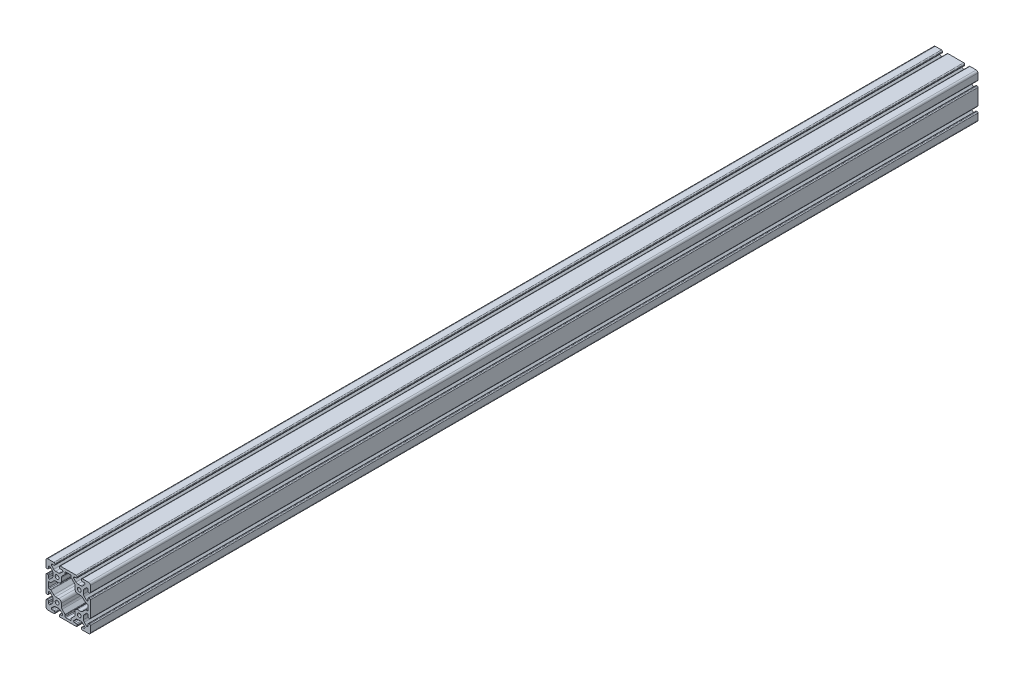
SolidWorks part; units mm, degrees
material "6061 Alloy"
ref_plane "Front Plane" through (0, 0, 0) normal (0, 0, 1) x (1, 0, 0)
ref_plane "Top Plane" through (0, 0, 0) normal (0, 1, 0) x (1, 0, 0)
ref_plane "Right Plane" through (0, 0, 0) normal (1, 0, 0) x (0, 0, -1)
sketch "Sketch1" plane through (0, 0, 0) normal (0, 0, 1) x (1, 0, 0)
  line L0 (0, -40) -> (0, 40) construction
  line L1 (0, 0) -> (-43.5804, 43.5804) construction
  line L2 (-20, 20) -> (-47.7323, 20) construction
  line L3 (-20, 20) -> (3.796, 43.796) construction
  line L4 (-20, 20) -> (-20, 43.5758) construction
  line L5 (-20, -27.7) -> (-20, -47.5576) construction
  line L7 (-36.8718, 24) -> (-28.8718, 24) construction
  line L8 (-36.8718, 24) -> (-36.8718, 16) construction
  line L9 (-36.8718, 16) -> (-28.8718, 16) construction
  line L10 (-28.8718, 24) -> (-28.8718, 16) construction
  line L11 (-36.8718, 24) -> (-28.8718, 16) construction
  line L12 (-36.8718, 16) -> (-28.8718, 24) construction
  line L131 (29.0912, 26.0365) -> (33.0827, 30.028)
  line L132 (27.7, 17.3222) -> (27.7, 22.6778)
  line L133 (29.0912, 13.9635) -> (33.0827, 9.972)
  line L134 (33.6201, 9.7494) -> (34.11, 9.7494)
  line L135 (35.68, 11.3194) -> (35.68, 14.2221)
  line L136 (37.25, 15.7921) -> (38.43, 15.7921)
  line L137 (40, 14.2221) -> (40, 7.0214)
  line L138 (40, 7.0214) -> (40, -7.0214)
  line L139 (40, -7.0214) -> (40, -14.2221)
  line L140 (38.43, -15.7921) -> (37.25, -15.7921)
  line L141 (35.68, -14.2221) -> (35.68, -11.3194)
  line L142 (33.6201, -9.7494) -> (34.11, -9.7494)
  line L143 (29.0912, -13.9635) -> (33.0827, -9.972)
  line L144 (27.7, -22.6778) -> (27.7, -17.3222)
  line L145 (29.0912, -26.0365) -> (33.0827, -30.028)
  line L146 (33.6201, -30.2506) -> (34.11, -30.2506)
  line L147 (35.68, -28.6806) -> (35.68, -25.7779)
  line L148 (37.25, -24.2079) -> (38.43, -24.2079)
  line L149 (40, -25.7779) -> (40, -33.0259)
  line L150 (40, -33.0259) -> (40, -36.83)
  line L151 (36.83, -40) -> (32.9998, -40)
  line L152 (32.9998, -40) -> (25.5696, -40)
  line L153 (23.9996, -38.43) -> (23.9996, -37.25)
  line L154 (25.5696, -35.68) -> (28.4723, -35.68)
  line L155 (30.0413, -34.0552) -> (30.0171, -33.3605)
  line L156 (29.7949, -32.8496) -> (26.0365, -29.0912)
  line L157 (17.3222, -27.7) -> (22.6778, -27.7)
  line L158 (10.035, -33.0197) -> (13.9635, -29.0912)
  line L159 (9.8124, -33.8926) -> (9.8124, -33.5571)
  line L160 (11.3824, -35.4626) -> (14.4246, -35.4626)
  line L161 (15.9946, -37.0326) -> (15.9946, -38.43)
  line L162 (14.4246, -40) -> (6.9987, -40)
  line L163 (6.9987, -40) -> (-6.9987, -40)
  line L164 (-6.9987, -40) -> (-14.4292, -40)
  line L165 (-15.9992, -38.43) -> (-15.9992, -37.25)
  line L166 (-14.4292, -35.68) -> (-11.5265, -35.68)
  line L167 (-9.9574, -34.0552) -> (-9.9816, -33.3618)
  line L168 (-10.2038, -32.8509) -> (-13.9635, -29.0912)
  line L169 (-22.6778, -27.7) -> (-17.3222, -27.7)
  line L170 (-30.028, -33.0827) -> (-26.0365, -29.0912)
  line L171 (-30.2506, -34.11) -> (-30.2506, -33.6201)
  line L172 (-28.6806, -35.68) -> (-25.7231, -35.68)
  line L173 (-24.1531, -37.25) -> (-24.1531, -38.43)
  line L174 (-25.7231, -40) -> (-33, -40)
  line L175 (-33, -40) -> (-36.83, -40)
  line L176 (-40, -36.83) -> (-40, -33.0191)
  line L177 (-40, -33.0191) -> (-40, -25.591)
  line L178 (-38.43, -24.021) -> (-37.25, -24.021)
  line L179 (-35.68, -28.4937) -> (-35.68, -25.591)
  line L180 (-34.0552, -30.0627) -> (-33.3827, -30.0392)
  line L181 (-32.8718, -29.8171) -> (-29.0912, -26.0365)
  line L182 (-27.7, -22.6778) -> (-27.7, -17.3222)
  line L183 (-29.0912, -13.9635) -> (-33.0827, -9.972)
  line L184 (-34.11, -9.7494) -> (-33.6201, -9.7494)
  line L185 (-35.68, -11.3194) -> (-35.68, -14.4473)
  line L186 (-38.43, -16.0173) -> (-37.25, -16.0173)
  line L187 (-40, -14.4473) -> (-40, -7.0169)
  line L188 (-40, -7.0169) -> (-40, 7.0169)
  line L189 (-40, 7.0169) -> (-40, 14.1348)
  line L190 (-38.1948, 15.94) -> (-36.9772, 15.94)
  line L191 (-35.68, 11.3194) -> (-35.68, 14.6428)
  line L192 (-34.11, 9.7494) -> (-33.6201, 9.7494)
  line L193 (-33.0827, 9.972) -> (-29.0912, 13.9635)
  line L194 (-27.7, 17.3222) -> (-27.7, 22.6778)
  line L195 (-29.0912, 26.0365) -> (-33.0827, 30.028)
  line L196 (-34.11, 30.2506) -> (-33.6201, 30.2506)
  line L197 (-35.68, 28.6806) -> (-35.68, 25.3572)
  line L198 (-38.1948, 24.06) -> (-36.9772, 24.06)
  line L199 (-40, 25.8652) -> (-40, 33.3181)
  line L200 (-40, 33.3181) -> (-40, 36.83)
  line L201 (-36.83, 40) -> (-33.0314, 40)
  line L202 (-33.0314, 40) -> (-25.8652, 40)
  line L203 (-24.06, 36.9772) -> (-24.06, 38.1948)
  line L204 (-25.3572, 35.68) -> (-28.7018, 35.68)
  line L205 (-30.285, 33.6069) -> (-30.285, 34.0968)
  line L206 (-30.0961, 33.1508) -> (-26.0365, 29.0912)
  line L207 (-22.6778, 27.7) -> (-17.3222, 27.7)
  line L208 (-13.9635, 29.0912) -> (-9.9039, 33.1508)
  line L209 (-9.715, 33.6069) -> (-9.715, 34.0968)
  line L210 (-14.6428, 35.68) -> (-11.2982, 35.68)
  line L211 (-15.94, 36.9772) -> (-15.94, 38.1948)
  line L212 (-14.1348, 40) -> (-6.9844, 40)
  line L213 (-6.9844, 40) -> (6.9844, 40)
  line L214 (6.9844, 40) -> (14.1348, 40)
  line L215 (15.94, 36.9772) -> (15.94, 38.1948)
  line L216 (14.6428, 35.68) -> (11.2982, 35.68)
  line L217 (9.715, 33.6069) -> (9.715, 34.0968)
  line L218 (9.9039, 33.1508) -> (13.9635, 29.0912)
  line L219 (17.3222, 27.7) -> (22.6778, 27.7)
  line L220 (26.0365, 29.0912) -> (30.028, 33.0827)
  line L221 (30.2506, 33.6201) -> (30.2506, 34.11)
  line L222 (25.5409, 35.679) -> (28.6258, 35.679)
  line L223 (23.9709, 37.249) -> (23.9709, 38.43)
  line L224 (25.5409, 40) -> (36.83, 40)
  line L226 (40, 36.83) -> (40, 32.9339)
  line L227 (40, 32.9339) -> (40, 25.7779)
  line L228 (38.43, 24.2079) -> (37.0956, 24.2079)
  line L229 (35.5256, 25.7779) -> (35.5256, 28.6806)
  line L230 (33.6201, 30.2506) -> (33.9556, 30.2506)
  line L231 (17.07, 12.32) -> (22.6578, 12.32)
  line L232 (26.0165, 10.9288) -> (31.1439, 5.8014)
  line L233 (32.0419, 5.4294) -> (34.41, 5.4294)
  line L234 (35.68, -4.1594) -> (35.68, 4.1594)
  line L235 (32.0419, -5.4294) -> (34.41, -5.4294)
  line L236 (26.0165, -10.9288) -> (31.1439, -5.8014)
  line L237 (17.07, -12.32) -> (22.6578, -12.32)
  line L238 (12.32, -22.6578) -> (12.32, -17.07)
  line L239 (5.8014, -31.1439) -> (10.9288, -26.0165)
  line L240 (5.4294, -34.41) -> (5.4294, -32.0419)
  line L241 (-4.1594, -35.68) -> (4.1594, -35.68)
  line L242 (-5.4294, -34.41) -> (-5.4294, -32.0419)
  line L243 (-5.8014, -31.1439) -> (-10.9288, -26.0165)
  line L244 (-12.32, -22.6578) -> (-12.32, -17.07)
  line L245 (-22.6578, -12.32) -> (-17.07, -12.32)
  line L246 (-26.0165, -10.9288) -> (-31.1439, -5.8014)
  line L247 (-34.41, -5.4294) -> (-32.0419, -5.4294)
  line L248 (-35.68, -4.1594) -> (-35.68, 4.1594)
  line L249 (-34.41, 5.4294) -> (-32.0419, 5.4294)
  line L250 (-31.1439, 5.8014) -> (-26.0165, 10.9288)
  line L251 (-22.6578, 12.32) -> (-17.07, 12.32)
  line L252 (-12.32, 17.07) -> (-12.32, 22.6578)
  line L253 (-10.9288, 26.0165) -> (-5.8014, 31.1439)
  line L254 (-5.4294, 32.0419) -> (-5.4294, 34.41)
  line L255 (-4.1594, 35.68) -> (4.1594, 35.68)
  line L256 (5.4294, 32.0419) -> (5.4294, 34.41)
  line L257 (5.8014, 31.1439) -> (10.9288, 26.0165)
  line L258 (12.32, 17.07) -> (12.32, 22.6578)
  line L260 (-40, 0) -> (40, 0) construction
  circle A0 centre (-32.8718, 20) radius 4 construction
  circle A116 centre (-20, 20) radius 3.4
  circle A117 centre (20, 20) radius 3.4
  circle A118 centre (20, -20) radius 3.4
  circle A119 centre (-20, -20) radius 3.4
  arc A120 (29.0912, 26.0365) -> (27.7, 22.6778) centre (32.45, 22.6778) ccw
  arc A121 (27.7, 17.3222) -> (29.0912, 13.9635) centre (32.45, 17.3222) ccw
  arc A122 (33.0827, 9.972) -> (33.6201, 9.7494) centre (33.6201, 10.5094) ccw
  arc A123 (34.11, 9.7494) -> (35.68, 11.3194) centre (34.11, 11.3194) ccw
  arc A124 (37.25, 15.7921) -> (35.68, 14.2221) centre (37.25, 14.2221) ccw
  arc A125 (40, 14.2221) -> (38.43, 15.7921) centre (38.43, 14.2221) ccw
  arc A126 (38.43, -15.7921) -> (40, -14.2221) centre (38.43, -14.2221) ccw
  arc A127 (35.68, -14.2221) -> (37.25, -15.7921) centre (37.25, -14.2221) ccw
  arc A128 (35.68, -11.3194) -> (34.11, -9.7494) centre (34.11, -11.3194) ccw
  arc A129 (33.6201, -9.7494) -> (33.0827, -9.972) centre (33.6201, -10.5094) ccw
  arc A130 (29.0912, -13.9635) -> (27.7, -17.3222) centre (32.45, -17.3222) ccw
  arc A131 (27.7, -22.6778) -> (29.0912, -26.0365) centre (32.45, -22.6778) ccw
  arc A132 (33.0827, -30.028) -> (33.6201, -30.2506) centre (33.6201, -29.4906) ccw
  arc A133 (34.11, -30.2506) -> (35.68, -28.6806) centre (34.11, -28.6806) ccw
  arc A134 (37.25, -24.2079) -> (35.68, -25.7779) centre (37.25, -25.7779) ccw
  arc A135 (40, -25.7779) -> (38.43, -24.2079) centre (38.43, -25.7779) ccw
  arc A136 (36.83, -40) -> (40, -36.83) centre (36.83, -36.83) ccw
  arc A137 (23.9996, -38.43) -> (25.5696, -40) centre (25.5696, -38.43) ccw
  arc A138 (25.5696, -35.68) -> (23.9996, -37.25) centre (25.5696, -37.25) ccw
  arc A139 (28.4723, -35.68) -> (30.0413, -34.0552) centre (28.4723, -34.11) ccw
  arc A140 (30.0171, -33.3605) -> (29.7949, -32.8496) centre (29.2575, -33.387) ccw
  arc A141 (26.0365, -29.0912) -> (22.6778, -27.7) centre (22.6778, -32.45) ccw
  arc A142 (17.3222, -27.7) -> (13.9635, -29.0912) centre (17.3222, -32.45) ccw
  arc A143 (10.035, -33.0197) -> (9.8124, -33.5571) centre (10.5724, -33.5571) ccw
  arc A144 (9.8124, -33.8926) -> (11.3824, -35.4626) centre (11.3824, -33.8926) ccw
  arc A145 (15.9946, -37.0326) -> (14.4246, -35.4626) centre (14.4246, -37.0326) ccw
  arc A146 (14.4246, -40) -> (15.9946, -38.43) centre (14.4246, -38.43) ccw
  arc A147 (-15.9992, -38.43) -> (-14.4292, -40) centre (-14.4292, -38.43) ccw
  arc A148 (-14.4292, -35.68) -> (-15.9992, -37.25) centre (-14.4292, -37.25) ccw
  arc A149 (-11.5265, -35.68) -> (-9.9574, -34.0552) centre (-11.5265, -34.11) ccw
  arc A150 (-9.9816, -33.3618) -> (-10.2038, -32.8509) centre (-10.7412, -33.3883) ccw
  arc A151 (-13.9635, -29.0912) -> (-17.3222, -27.7) centre (-17.3222, -32.45) ccw
  arc A152 (-22.6778, -27.7) -> (-26.0365, -29.0912) centre (-22.6778, -32.45) ccw
  arc A153 (-30.028, -33.0827) -> (-30.2506, -33.6201) centre (-29.4906, -33.6201) ccw
  arc A154 (-30.2506, -34.11) -> (-28.6806, -35.68) centre (-28.6806, -34.11) ccw
  arc A155 (-24.1531, -37.25) -> (-25.7231, -35.68) centre (-25.7231, -37.25) ccw
  arc A156 (-25.7231, -40) -> (-24.1531, -38.43) centre (-25.7231, -38.43) ccw
  arc A157 (-40, -36.83) -> (-36.83, -40) centre (-36.83, -36.83) ccw
  arc A158 (-38.43, -24.021) -> (-40, -25.591) centre (-38.43, -25.591) ccw
  arc A159 (-35.68, -25.591) -> (-37.25, -24.021) centre (-37.25, -25.591) ccw
  arc A160 (-35.68, -28.4937) -> (-34.0552, -30.0627) centre (-34.11, -28.4937) ccw
  arc A161 (-33.3827, -30.0392) -> (-32.8718, -29.8171) centre (-33.4092, -29.2797) ccw
  arc A162 (-29.0912, -26.0365) -> (-27.7, -22.6778) centre (-32.45, -22.6778) ccw
  arc A163 (-27.7, -17.3222) -> (-29.0912, -13.9635) centre (-32.45, -17.3222) ccw
  arc A164 (-33.0827, -9.972) -> (-33.6201, -9.7494) centre (-33.6201, -10.5094) ccw
  arc A165 (-34.11, -9.7494) -> (-35.68, -11.3194) centre (-34.11, -11.3194) ccw
  arc A166 (-37.25, -16.0173) -> (-35.68, -14.4473) centre (-37.25, -14.4473) ccw
  arc A167 (-40, -14.4473) -> (-38.43, -16.0173) centre (-38.43, -14.4473) ccw
  arc A168 (-38.1948, 15.94) -> (-40, 14.1348) centre (-38.1948, 14.1348) ccw
  arc A169 (-35.68, 14.6428) -> (-36.9772, 15.94) centre (-36.9772, 14.6428) ccw
  arc A170 (-35.68, 11.3194) -> (-34.11, 9.7494) centre (-34.11, 11.3194) ccw
  arc A171 (-33.6201, 9.7494) -> (-33.0827, 9.972) centre (-33.6201, 10.5094) ccw
  arc A172 (-29.0912, 13.9635) -> (-27.7, 17.3222) centre (-32.45, 17.3222) ccw
  arc A173 (-27.7, 22.6778) -> (-29.0912, 26.0365) centre (-32.45, 22.6778) ccw
  arc A174 (-33.0827, 30.028) -> (-33.6201, 30.2506) centre (-33.6201, 29.4906) ccw
  arc A175 (-34.11, 30.2506) -> (-35.68, 28.6806) centre (-34.11, 28.6806) ccw
  arc A176 (-36.9772, 24.06) -> (-35.68, 25.3572) centre (-36.9772, 25.3572) ccw
  arc A177 (-40, 25.8652) -> (-38.1948, 24.06) centre (-38.1948, 25.8652) ccw
  arc A178 (-36.83, 40) -> (-40, 36.83) centre (-36.83, 36.83) ccw
  arc A179 (-24.06, 38.1948) -> (-25.8652, 40) centre (-25.8652, 38.1948) ccw
  arc A180 (-25.3572, 35.68) -> (-24.06, 36.9772) centre (-25.3572, 36.9772) ccw
  arc A181 (-28.7018, 35.68) -> (-30.285, 34.0968) centre (-28.7018, 34.0968) ccw
  arc A182 (-30.285, 33.6069) -> (-30.0961, 33.1508) centre (-29.6399, 33.6069) ccw
  arc A183 (-26.0365, 29.0912) -> (-22.6778, 27.7) centre (-22.6778, 32.45) ccw
  arc A184 (-17.3222, 27.7) -> (-13.9635, 29.0912) centre (-17.3222, 32.45) ccw
  arc A185 (-9.9039, 33.1508) -> (-9.715, 33.6069) centre (-10.3601, 33.6069) ccw
  arc A186 (-9.715, 34.0968) -> (-11.2982, 35.68) centre (-11.2982, 34.0968) ccw
  arc A187 (-15.94, 36.9772) -> (-14.6428, 35.68) centre (-14.6428, 36.9772) ccw
  arc A188 (-14.1348, 40) -> (-15.94, 38.1948) centre (-14.1348, 38.1948) ccw
  arc A189 (15.94, 38.1948) -> (14.1348, 40) centre (14.1348, 38.1948) ccw
  arc A190 (14.6428, 35.68) -> (15.94, 36.9772) centre (14.6428, 36.9772) ccw
  arc A191 (11.2982, 35.68) -> (9.715, 34.0968) centre (11.2982, 34.0968) ccw
  arc A192 (9.715, 33.6069) -> (9.9039, 33.1508) centre (10.3601, 33.6069) ccw
  arc A193 (13.9635, 29.0912) -> (17.3222, 27.7) centre (17.3222, 32.45) ccw
  arc A194 (22.6778, 27.7) -> (26.0365, 29.0912) centre (22.6778, 32.45) ccw
  arc A195 (30.028, 33.0827) -> (30.2506, 33.6201) centre (29.4906, 33.6201) ccw
  arc A196 (30.2506, 34.11) -> (28.6258, 35.679) centre (28.6806, 34.11) ccw
  arc A197 (23.9709, 37.249) -> (25.5409, 35.679) centre (25.5409, 37.249) ccw
  arc A198 (25.5409, 40) -> (23.9709, 38.43) centre (25.5409, 38.43) ccw
  arc A199 (40, 36.83) -> (36.83, 40) centre (36.83, 36.83) ccw
  arc A200 (38.43, 24.2079) -> (40, 25.7779) centre (38.43, 25.7779) ccw
  arc A201 (35.5256, 25.7779) -> (37.0956, 24.2079) centre (37.0956, 25.7779) ccw
  arc A202 (35.5256, 28.6806) -> (33.9556, 30.2506) centre (33.9556, 28.6806) ccw
  arc A203 (33.6201, 30.2506) -> (33.0827, 30.028) centre (33.6201, 29.4906) ccw
  arc A204 (26.0165, 10.9288) -> (22.6578, 12.32) centre (22.6578, 7.57) ccw
  arc A205 (31.1439, 5.8014) -> (32.0419, 5.4294) centre (32.0419, 6.6994) ccw
  arc A206 (35.68, 4.1594) -> (34.41, 5.4294) centre (34.41, 4.1594) ccw
  arc A207 (34.41, -5.4294) -> (35.68, -4.1594) centre (34.41, -4.1594) ccw
  arc A208 (32.0419, -5.4294) -> (31.1439, -5.8014) centre (32.0419, -6.6994) ccw
  arc A209 (22.6578, -12.32) -> (26.0165, -10.9288) centre (22.6578, -7.57) ccw
  arc A210 (17.07, -12.32) -> (12.32, -17.07) centre (17.07, -17.07) ccw
  arc A211 (10.9288, -26.0165) -> (12.32, -22.6578) centre (7.57, -22.6578) ccw
  arc A212 (5.8014, -31.1439) -> (5.4294, -32.0419) centre (6.6994, -32.0419) ccw
  arc A213 (4.1594, -35.68) -> (5.4294, -34.41) centre (4.1594, -34.41) ccw
  arc A214 (-5.4294, -34.41) -> (-4.1594, -35.68) centre (-4.1594, -34.41) ccw
  arc A215 (-5.4294, -32.0419) -> (-5.8014, -31.1439) centre (-6.6994, -32.0419) ccw
  arc A216 (-12.32, -22.6578) -> (-10.9288, -26.0165) centre (-7.57, -22.6578) ccw
  arc A217 (-12.32, -17.07) -> (-17.07, -12.32) centre (-17.07, -17.07) ccw
  arc A218 (-26.0165, -10.9288) -> (-22.6578, -12.32) centre (-22.6578, -7.57) ccw
  arc A219 (-31.1439, -5.8014) -> (-32.0419, -5.4294) centre (-32.0419, -6.6994) ccw
  arc A220 (-35.68, -4.1594) -> (-34.41, -5.4294) centre (-34.41, -4.1594) ccw
  arc A221 (-34.41, 5.4294) -> (-35.68, 4.1594) centre (-34.41, 4.1594) ccw
  arc A222 (-32.0419, 5.4294) -> (-31.1439, 5.8014) centre (-32.0419, 6.6994) ccw
  arc A223 (-22.6578, 12.32) -> (-26.0165, 10.9288) centre (-22.6578, 7.57) ccw
  arc A224 (-17.07, 12.32) -> (-12.32, 17.07) centre (-17.07, 17.07) ccw
  arc A225 (-10.9288, 26.0165) -> (-12.32, 22.6578) centre (-7.57, 22.6578) ccw
  arc A226 (-5.8014, 31.1439) -> (-5.4294, 32.0419) centre (-6.6994, 32.0419) ccw
  arc A227 (-4.1594, 35.68) -> (-5.4294, 34.41) centre (-4.1594, 34.41) ccw
  arc A228 (5.4294, 34.41) -> (4.1594, 35.68) centre (4.1594, 34.41) ccw
  arc A229 (5.4294, 32.0419) -> (5.8014, 31.1439) centre (6.6994, 32.0419) ccw
  arc A230 (12.32, 22.6578) -> (10.9288, 26.0165) centre (7.57, 22.6578) ccw
  arc A231 (12.32, 17.07) -> (17.07, 12.32) centre (17.07, 17.07) ccw
  point P9 (-32.8718, 20)
  dimension "D8" = 6.8
  dimension "D1" = 80
  dimension "D2" = 40
  dimension "D3" = 20
  dimension "D4" = 20.57
  dimension "D5" = 4.32
  dimension "D6" = 4.32
  dimension "D7" = 8.12
  dimension "D9" = 4.32
  dimension "D10" = 12.3
  dimension "D11" = 8
  dimension "D12" = 8
extrude "Extrude1" add sketch "Sketch1" against normal blind 1600
